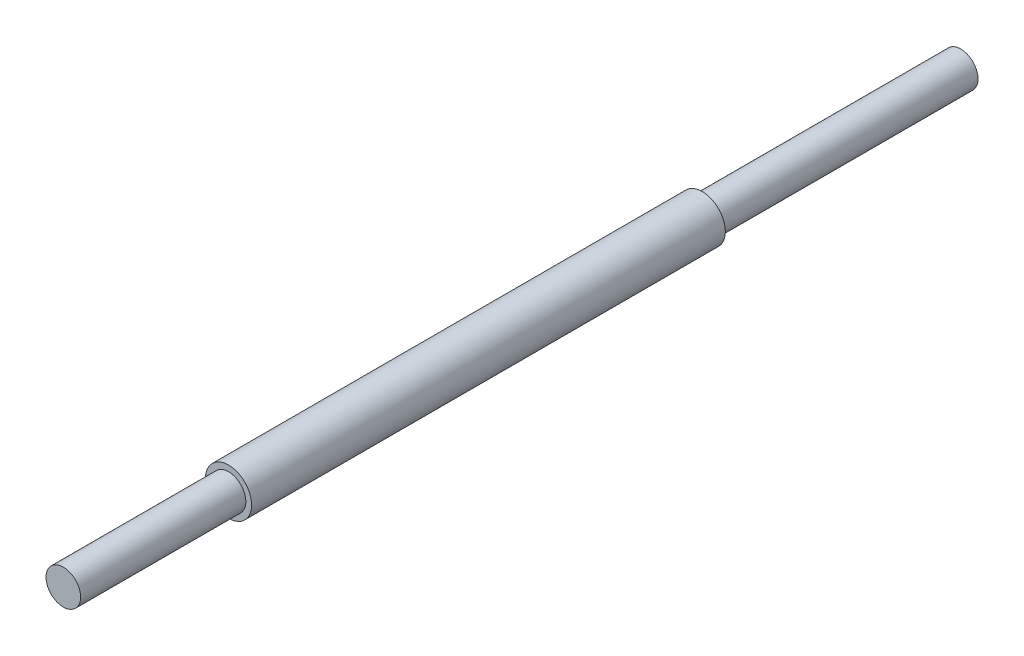
SolidWorks part; units mm, degrees
material "AISI 1020"
ref_plane "Front Plane" through (0, 0, 0) normal (0, 0, 1) x (1, 0, 0)
ref_plane "Top Plane" through (0, 0, 0) normal (0, 1, 0) x (1, 0, 0)
ref_plane "Right Plane" through (0, 0, 0) normal (1, 0, 0) x (0, 0, -1)
sketch "Sketch1" plane through (0, 0, 0) normal (0, 0, 1) x (1, 0, 0)
  circle A0 centre (0, 0) radius 6.35
  dimension "D1" = 12.7
extrude "Boss-Extrude1" add sketch "Sketch1" along normal blind 130.3528
sketch "Sketch2" plane through (0, 0, 130.3528) normal (0, 0, 1) x (1, 0, 0)
  circle A0 centre (0, 0) radius 4.7625
  dimension "D1" = 9.525
extrude "Boss-Extrude2" add sketch "Sketch2" along normal blind 45.466
sketch "Sketch3" plane through (0, 0, 0) normal (0, 0, -1) x (-1, 0, 0)
  circle A0 centre (0, 0) radius 4.7625
  dimension "D1" = 9.525
extrude "Boss-Extrude3" add sketch "Sketch3" along normal blind 71.12
sketch "Sketch4" plane through (0, 0, 0) normal (0, 1, 0) x (1, 0, 0)
  line L0 (4.7625, -175.8188) -> (4.7625, -176.0537)
  line L1 (52.578, -176.0537) -> (-52.578, -176.0537) construction
  line L2 (4.7625, -175.8188) -> (4.7625, -130.3528) construction
  line L3 (4.7625, -176.0537) -> (4.445, -176.0537)
  line L4 (4.445, -176.0537) -> (4.445, -175.8188)
  line L5 (-4.7625, -175.8188) -> (4.7625, -175.8188) construction
  line L6 (4.445, -175.8188) -> (4.7625, -175.8188)
  line L7 (0, -175.8188) -> (0, -171.0494) construction
  line L8 (0, -146.88) -> (0, -215.9928) construction
  dimension "D1" = 8.89
